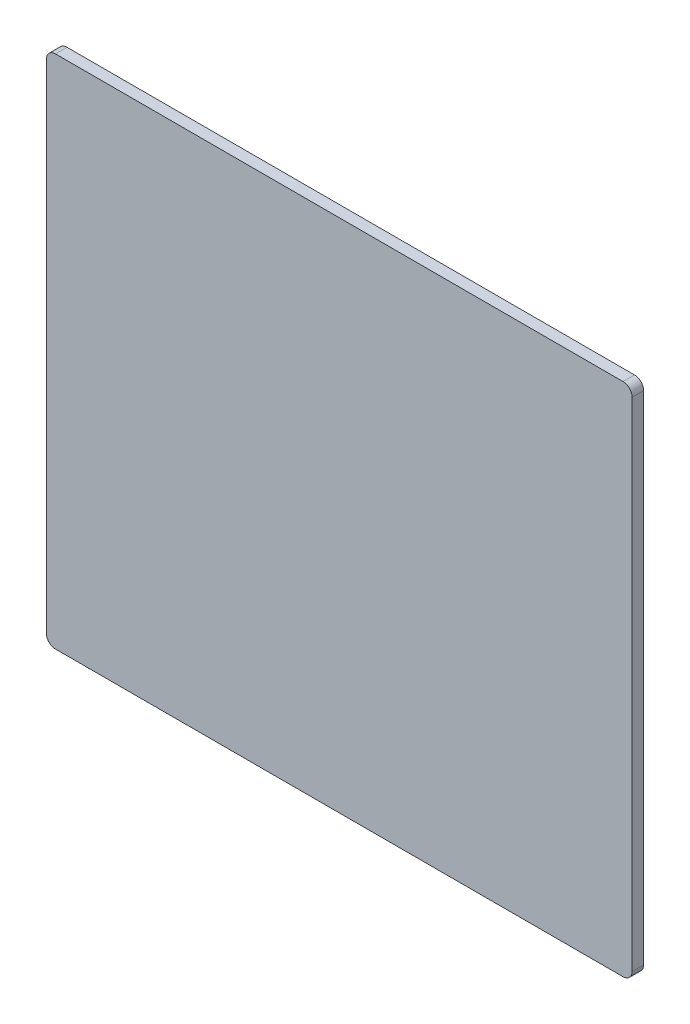
SolidWorks part; units mm, degrees
ref_plane "Front Plane" through (0, 0, 0) normal (0, 0, 1) x (1, 0, 0)
ref_plane "Top Plane" through (0, 0, 0) normal (0, 1, 0) x (1, 0, 0)
ref_plane "Right Plane" through (0, 0, 0) normal (1, 0, 0) x (0, 0, -1)
sketch "Sketch1" plane through (0, 0, 0) normal (0, 0, 1) x (1, 0, 0)
  line L1 (-476.498, 137.4676) -> (171.202, 137.4676)
  line L2 (-476.498, 137.4676) -> (-476.498, -432.5084)
  line L3 (-476.498, -432.5084) -> (171.202, -432.5084)
  line L4 (171.202, 137.4676) -> (171.202, -432.5084)
  dimension "D1" = 647.7
  dimension "D2" = 569.976
extrude "Boss-Extrude1" add sketch "Sketch1" along normal blind 12.7 contours L1 L4 L3 L2
fillet "Fillet1" radius 10 4 edges at (171.202, -432.5084, 6.35) (-476.498, -432.5084, 6.35) (-476.498, 137.4676, 6.35) (171.202, 137.4676, 6.35)
